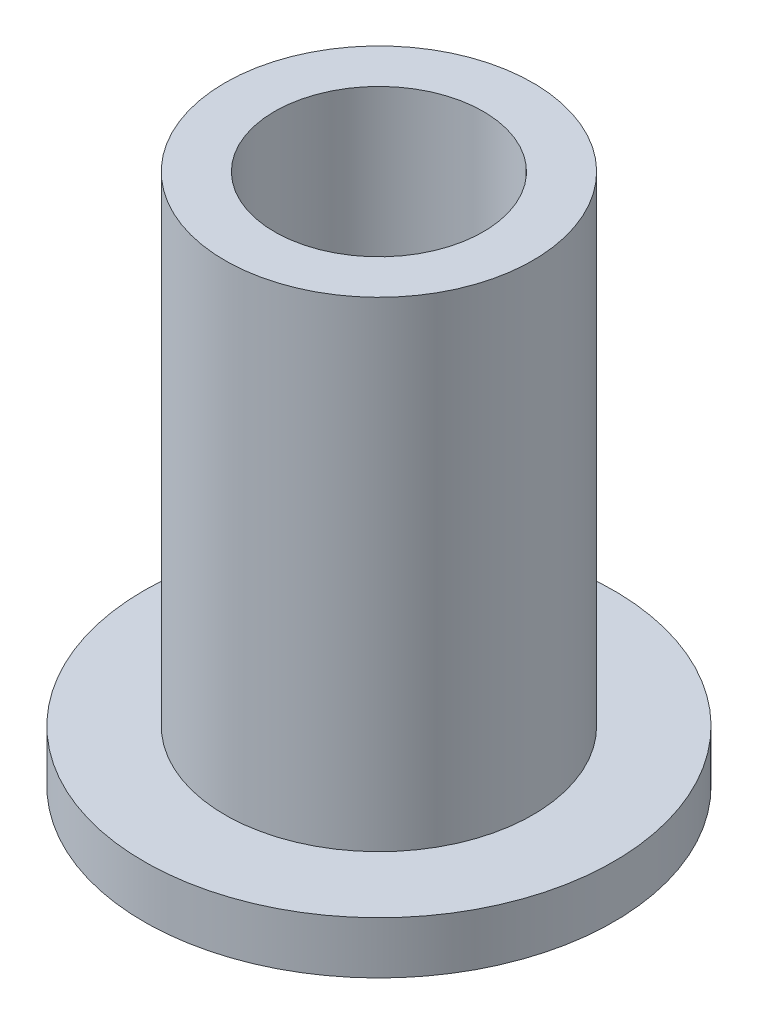
SolidWorks part; units mm, degrees
ref_plane "Front Plane" through (0, 0, 0) normal (0, 0, 1) x (1, 0, 0)
ref_plane "Top Plane" through (0, 0, 0) normal (0, 1, 0) x (1, 0, 0)
ref_plane "Right Plane" through (0, 0, 0) normal (1, 0, 0) x (0, 0, -1)
sketch "Sketch1" plane through (0, 0, 0) normal (0, 0, 1) x (1, 0, 0)
  line L0 (0, 9.8859) -> (0, -9.8859) construction
  line L1 (-2, -4.7) -> (-4.5, -4.7)
  line L2 (-4.5, -4.7) -> (-4.5, -3.7)
  line L3 (-4.5, -3.7) -> (-2.95, -3.7)
  line L9 (-2.95, -3.7) -> (-2.95, 5.5)
  line L10 (-2.95, 5.5) -> (-2, 5.5)
  line L11 (-2, 5.5) -> (-2, -4.7)
  dimension "D1" = 9
  dimension "D2" = 1
  dimension "D3" = 4
  dimension "D4" = 9.2
  dimension "D5" = 5.5
  dimension "D6" = 5.9
revolve "Revolve1" add sketch "Sketch1" angle 360 about L0
